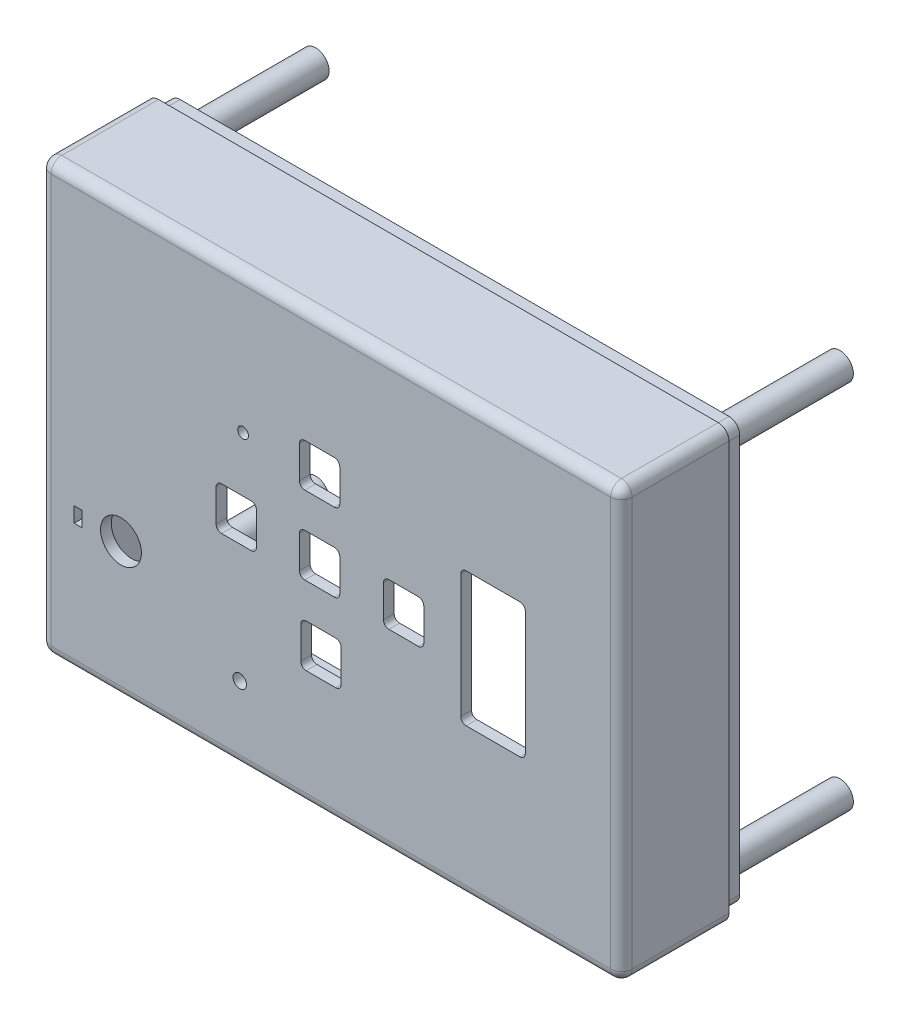
SolidWorks part; units mm, degrees
ref_plane "Front Plane" through (0, 0, 0) normal (0, 0, 1) x (1, 0, 0)
ref_plane "Top Plane" through (0, 0, 0) normal (0, 1, 0) x (1, 0, 0)
ref_plane "Right Plane" through (0, 0, 0) normal (1, 0, 0) x (0, 0, -1)
sketch "Sketch1" plane through (0, 0, 0) normal (0, 0, 1) x (1, 0, 0)
  line L5 (-31.944, -29.02) -> (-24.444, -29.02)
  line L7 (-31.944, -29.02) -> (-31.944, -37.02)
  line L8 (-31.944, -37.02) -> (-24.444, -37.02)
  line L9 (-32.198, -0.064) -> (-24.698, -0.064)
  line L10 (-32.198, -0.064) -> (-32.198, -8.064)
  line L11 (-32.198, -8.064) -> (-24.698, -8.064)
  line L12 (-24.698, -0.064) -> (-24.698, -8.064)
  line L13 (-32.198, -14.542) -> (-24.698, -14.542)
  line L14 (-32.198, -14.542) -> (-32.198, -22.542)
  line L15 (-32.198, -22.542) -> (-24.698, -22.542)
  line L16 (-24.698, -14.542) -> (-24.698, -22.542)
  line L17 (-47.692, -14.796) -> (-40.192, -14.796)
  line L18 (-47.692, -14.796) -> (-47.692, -22.796)
  line L19 (-47.692, -22.796) -> (-40.192, -22.796)
  line L20 (-40.192, -14.796) -> (-40.192, -22.796)
  line L21 (-16.577, -14.669) -> (-9.077, -14.669)
  line L22 (-16.577, -14.669) -> (-16.577, -22.669)
  line L23 (-16.577, -22.669) -> (-9.077, -22.669)
  line L24 (-9.077, -14.669) -> (-9.077, -22.669)
  line L25 (-24.444, -29.02) -> (-24.444, -37.02)
  line L26 (-2.2, -6.064) -> (9.8, -6.064)
  line L27 (-2.2, -6.064) -> (-2.2, -31.02)
  line L28 (-2.2, -31.02) -> (9.8, -31.02)
  line L29 (9.8, -6.064) -> (9.8, -31.02)
  line L31 (-74.0844, -32.038) -> (-72.5844, -32.038)
  line L32 (-74.0844, -32.038) -> (-74.0844, -34.838)
  line L33 (-74.0844, -34.838) -> (-72.5844, -34.838)
  line L34 (-72.5844, -32.038) -> (-72.5844, -34.838)
  circle A4 centre (-42.672, -4.572) radius 1
  circle A7 centre (-65.3841, -33.4079) radius 3.8
  point P4 (0, 0)
  point P5 (-28.448, -0.064)
  point P6 (-28.448, -22.542)
  dimension "D5" = 2
  dimension "D10" = 7.6
  dimension "D4" = 32.038
  dimension "D2" = 2.8
  dimension "D3" = 1.5
  dimension "D6" = 6
  dimension "D7" = 12
  dimension "D8" = 4.572
  dimension "D9" = 42.672
  dimension "D11" = 7.2003
  dimension "D12" = 6.478
  dimension "D13" = 8.121
  dimension "D14" = 7.994
  dimension "D15" = 6.732
  dimension "D16" = 6.605
  dimension "D17" = 6.478
  dimension "D18" = 8.248
  dimension "D19" = 7.867
  dimension "D20" = 0.064
  dimension "D21" = 24.698
  dimension "D22" = 6
  dimension "D23" = 9.8
  dimension "D24" = 32.198
  dimension "D25" = 8.064
  dimension "D26" = 24.698
  dimension "D27" = 9.077
  dimension "D28" = 47.692
  dimension "D29" = 22.796
  dimension "D30" = 22.542
  dimension "D31" = 22.669
  dimension "D32" = 37.02
sketch "Sketch2" plane through (0, 0, 0) normal (0, 0, 1) x (1, 0, 0)
  line L1 (-80.3841, 21.243) -> (27.674, 21.243)
  line L2 (-80.3841, 21.243) -> (-80.3841, -58.757)
  line L3 (-80.3841, -58.757) -> (27.674, -58.757)
  line L4 (27.674, 21.243) -> (27.674, -58.757)
  dimension "D1" = 80
  dimension "D2" = 27.674
  dimension "D3" = 58.757
  dimension "D4" = 80.3841
extrude "Boss-Extrude1" add sketch "Sketch2" along normal blind 5 and the other way blind 15
shell "Shell4" thickness 2
extrude "Cut-Extrude1" cut sketch "Sketch1" along normal blind 10
fillet "Fillet2" radius 2 8 edges at (-26.3551, 21.243, 5) (27.674, -18.757, 5) (-26.3551, -58.757, 5) (-80.3841, -18.757, 5) (-80.3841, 21.243, -5) (-80.3841, -58.757, -5) (27.674, -58.757, -5) (27.674, 21.243, -5)
fillet "Fillet3" radius 1 8 edges at (-78.3841, -56.757, -6) (-78.3841, 19.243, -6) (-78.3841, -18.757, 3) (-26.3551, 19.243, 3) (25.674, 19.243, -6) (25.674, -18.757, 3) (-26.3551, -56.757, 3) (25.674, -56.757, -6)
sketch "Sketch5" plane through (0, 0, 0) normal (0, 0, 1) x (1, 0, 0)
  circle A1 centre (22.3034, 15.6748) radius 2.5
  circle A2 centre (-75.1685, 15.6748) radius 2.5
  circle A3 centre (-75.1685, -53.2826) radius 2.5
  circle A4 centre (22.3034, -53.2826) radius 2.5
  dimension "D1" = 5
  dimension "D2" = 22.3034
  dimension "D3" = 15.6748
  dimension "D4" = 97.4719
  dimension "D5" = 68.9574
extrude "Boss-Extrude3" add sketch "Sketch5" against normal blind 41 separate body
sketch "Sketch6" plane through (0, 0, 0) normal (0, 0, 1) x (1, 0, 0)
  circle A0 centre (-43.3004, -44.8496) radius 1.25
  dimension "D1" = 2.5
  dimension "D2" = 44.8496
  dimension "D3" = 43.3004
extrude "Cut-Extrude2" cut sketch "Sketch6" along normal through all
sketch "Sketch7" plane through (0, 0, -15) normal (0, 0, -1) x (-1, 0, 0)
  line L0 (80.3841, 21.243) -> (-27.674, 21.243) construction
  line L1 (-26.674, 20.243) -> (79.3841, 20.243)
  line L2 (-26.674, 20.243) -> (-26.674, -57.757)
  line L3 (-26.674, -57.757) -> (79.3841, -57.757)
  line L4 (79.3841, 20.243) -> (79.3841, -57.757)
  line L5 (80.3841, 21.243) -> (80.3841, -58.757) construction
  line L6 (80.3841, -58.757) -> (-27.674, -58.757) construction
  line L7 (-27.674, 21.243) -> (-27.674, -58.757) construction
  line L8 (78.3841, 18.243) -> (78.3841, -55.757) construction
  line L9 (-24.674, 19.243) -> (77.3841, 19.243)
  line L10 (-25.674, 18.243) -> (-25.674, -55.757)
  line L11 (-24.674, -56.757) -> (77.3841, -56.757)
  line L12 (78.3841, 18.243) -> (78.3841, -55.757)
  line L13 (77.3841, -56.757) -> (-24.674, -56.757) construction
  line L14 (-24.674, 19.243) -> (77.3841, 19.243) construction
  line L15 (-25.674, -55.757) -> (-25.674, 18.243) construction
  arc A0 (-25.674, -55.757) -> (-24.674, -56.757) centre (-24.674, -55.757) ccw
  arc A1 (-24.674, 19.243) -> (-25.674, 18.243) centre (-24.674, 18.243) ccw
  arc A2 (77.3841, 19.243) -> (78.3841, 18.243) centre (77.3841, 18.243) cw
  arc A3 (77.3841, -56.757) -> (78.3841, -55.757) centre (77.3841, -55.757) ccw
  dimension "D9" = 1
  dimension "D10" = 1
  dimension "D1" = 1
  dimension "D2" = 1
  dimension "D3" = 1
  dimension "D4" = 1
  dimension "D5" = 0
  dimension "D6" = 0
  dimension "D7" = 0
  dimension "D8" = 0
extrude "Boss-Extrude4" add sketch "Sketch7" along normal blind 3
hole_wizard "#34 (0.111) Diameter Hole1" positions "3DSketch3" profile "Sketch9" hole size "#34" standard "ANSI Inch"
sketch3d "3DSketch3"
  line L0 (22.3034, -53.2826, -41) -> (22.3034, -53.2826, 0) construction
  line L1 (-75.1685, -53.2826, -41) -> (-75.1685, -53.2826, 0) construction
  line L2 (-75.1685, 15.6748, -41) -> (-75.1685, 15.6748, 0) construction
  line L3 (22.3034, 15.6748, -41) -> (22.3034, 15.6748, 0) construction
  point P0 (22.3034, -53.2826, -41)
  point P4 (-75.1685, -53.2826, -41)
  point P8 (-75.1685, 15.6748, -41)
  point P12 (22.3034, 15.6748, -41)
sketch "Sketch9" plane through (22.3034, -53.2826, -41) normal (1, 0, 0) x (0, 1, 0)
  line L0 (0, 0) -> (0, 15)
  line L1 (0, 15) -> (1.4097, 14.153)
  line L2 (1.4097, 14.153) -> (1.4097, 0)
  line L5 (1.4097, 0) -> (0, 0)
  line L10 (0, 15) -> (-1.4097, 14.153) construction
  line L11 (0, -6.35) -> (0, 107.95) construction
  dimension "Hole Dia." = 2.8194
  dimension "Hole Depth" = 15
  dimension "Drill Angle" = 118
sketch "Sketch11" plane through (0, 0, 3) normal (0, 0, -1) x (-1, 0, 0)
  circle A0 centre (50.165, 1.5756) radius 2.9
  circle A1 centre (50.165, -52.451) radius 2.9
  circle A2 centre (-13.716, -7.366) radius 2.9
  circle A3 centre (-13.716, -36.576) radius 2.9
  point P6 (-13.716, -36.576)
  point P7 (0, 0)
  point P8 (0, 0)
  point P9 (16.4172, 21.243)
  point P12 (11.3571, -2.5749)
  dimension "D1" = 5.8
  dimension "D2" = 5.8
  dimension "D3" = 5.8
  dimension "D4" = 5.8
  dimension "D5" = 13.716
  dimension "D6" = 7.366
  dimension "D7" = 29.21
  dimension "D8" = 54.0266
  dimension "D9" = 50.165
  dimension "D10" = 1.5756
extrude "Boss-Extrude5" add sketch "Sketch11" along normal blind 10
hole_wizard "CSK for #2 Flat Head Machine Screw (100)1" positions "3DSketch11" profile "Sketch12" countersink size "#2" standard "ANSI Inch"
sketch3d "3DSketch11"
  line L0 (13.716, -7.366, -7) -> (13.716, -7.366, 3) construction
  line L1 (13.716, -36.576, -7) -> (13.716, -36.576, 3) construction
  line L2 (-50.165, -52.451, -7) -> (-50.165, -52.451, 3) construction
  line L3 (-50.165, 1.5756, -7) -> (-50.165, 1.5756, 3) construction
  point P0 (13.716, -7.366, -7)
  point P4 (13.716, -36.576, -7)
  point P8 (-50.165, -52.451, -7)
  point P12 (-50.165, 1.5756, -7)
sketch "Sketch12" plane through (13.716, -7.366, -7) normal (1, 0, 0) x (0, 1, 0)
  line L0 (0, 0) -> (0, 5)
  line L1 (0, 5) -> (1.2192, 4.2674)
  line L2 (1.2192, 4.2674) -> (1.2192, 0.8099)
  line L3 (1.2192, 0.8099) -> (2.1844, 0)
  line L5 (2.1844, 0) -> (0, 0)
  line L6 (-1.2192, 0.8099) -> (-2.1844, 0) construction
  line L10 (0, 5) -> (-1.2192, 4.2674) construction
  line L11 (0, -6.35) -> (0, 107.95) construction
  dimension "Hole Dia." = 2.4384
  dimension "Hole Depth" = 5
  dimension "Near C'Sink Dia." = 4.3688
  dimension "Near C'Sink Angle" = 100
  dimension "Drill Angle" = 118
fillet "Fillet4" radius 1 24 edges at (-24.698, -8.064, 4) (-24.698, -0.064, 4) (-32.198, -8.064, 4) (-32.198, -22.542, 4) (-24.698, -22.542, 4) (-24.444, -37.02, 4) (-24.698, -14.542, 4) (-24.444, -29.02, 4) (-31.944, -37.02, 4) (-16.577, -22.669, 4) (-9.077, -22.669, 4) (-9.077, -14.669, 4) (-2.2, -31.02, 4) (9.8, -31.02, 4) (9.8, -6.064, 4) (-2.2, -6.064, 4) (-16.577, -14.669, 4) (-31.944, -29.02, 4) (-32.198, -0.064, 4) (-32.198, -14.542, 4) (-40.192, -22.796, 4) (-40.192, -14.796, 4) (-47.692, -14.796, 4) (-47.692, -22.796, 4)
fillet "Fillet5" radius 2 4 edges at (-79.3841, 20.243, -16.5) (26.674, 20.243, -16.5) (26.674, -57.757, -16.5) (-79.3841, -57.757, -16.5)
